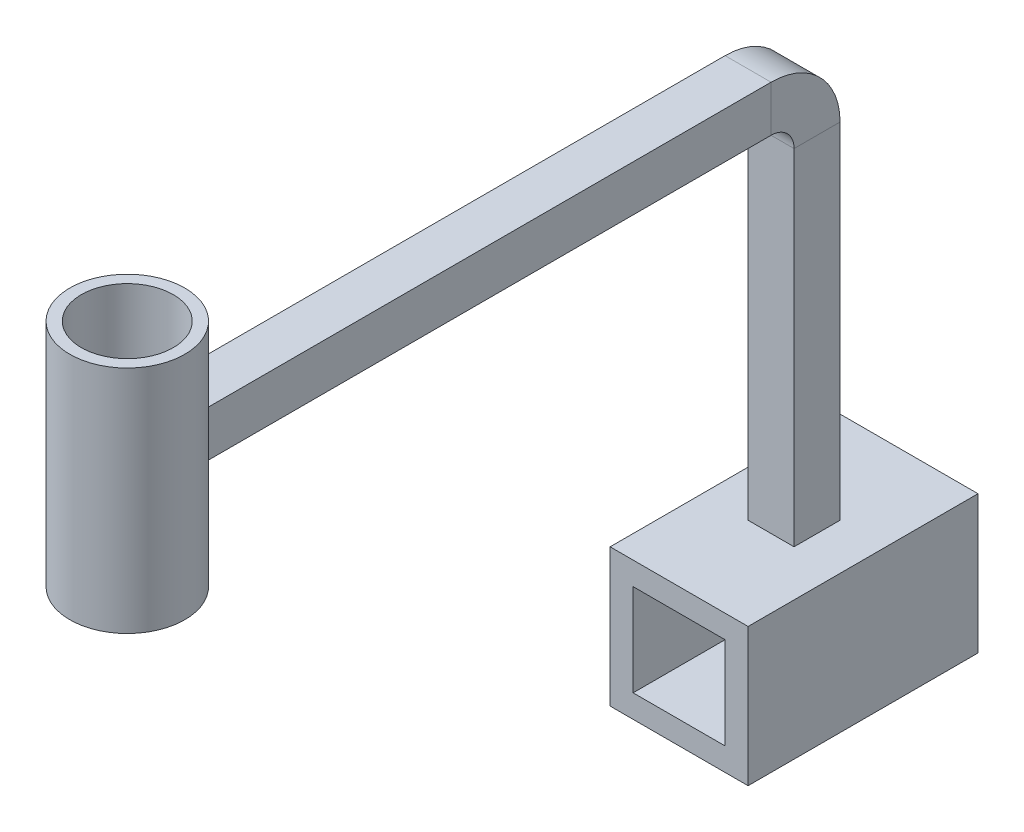
SolidWorks part; units mm, degrees
ref_plane "Plan de face" through (0, 0, 0) normal (0, 0, 1) x (1, 0, 0)
ref_plane "Plan de dessus" through (0, 0, 0) normal (0, 1, 0) x (1, 0, 0)
ref_plane "Plan de droite" through (0, 0, 0) normal (1, 0, 0) x (0, 0, -1)
sketch "Esquisse1" plane through (0, 0, 0) normal (0, 0, 1) x (1, 0, 0)
  line L1 (-2, 2) -> (2, 2)
  line L2 (-2, 2) -> (-2, -2)
  line L3 (-2, -2) -> (2, -2)
  line L4 (2, 2) -> (2, -2)
  line L5 (-2, 2) -> (2, -2) construction
  line L6 (-2, -2) -> (2, 2) construction
  line L7 (-3, 3) -> (3, 3)
  line L8 (-3, 3) -> (-3, -3)
  line L9 (-3, -3) -> (3, -3)
  line L10 (3, 3) -> (3, -3)
  line L11 (-3, 3) -> (3, -3) construction
  line L12 (-3, -3) -> (3, 3) construction
  point P0 (0, 0)
  point P6 (0, 0)
  dimension "D1" = 4
  dimension "D2" = 4
  dimension "D3" = 6
  dimension "D4" = 6
extrude "Boss.-Extru.1" add sketch "Esquisse1" along normal blind 10
sketch "Esquisse2" plane through (0, 3, 0) normal (0, 1, 0) x (1, 0, 0)
  line L0 (0, 0) -> (0, -11.0721) construction
  line L1 (1, -6) -> (-1, -6)
  line L2 (1, -6) -> (1, -4)
  line L3 (1, -4) -> (-1, -4)
  line L4 (-1, -6) -> (-1, -4)
  line L5 (1, -6) -> (-1, -4) construction
  line L6 (1, -4) -> (-1, -6) construction
  line L7 (3, 0) -> (-3, 0) construction
  line L10 (-7.7593, -5) -> (11.5662, -5) construction
  line L11 (3, -10) -> (-3, -10) construction
  point P0 (0, -5)
  point P13 (0, 0)
  dimension "D3" = 2
  dimension "D4" = 2
sketch "Esquisse3" plane through (0, 0, 0) normal (1, 0, 0) x (0, 0, -1)
  line L0 (-5, 3) -> (-5, 18)
  line L1 (-4, 3) -> (-6, 3) construction
  line L2 (-7, 20) -> (-32, 20)
  arc A0 (-5, 18) -> (-7, 20) centre (-7, 18) ccw
  dimension "D1" = 2
  dimension "D2" = 15
  dimension "D3" = 25
sweep "Balayage1" add profiles "Esquisse2" path "Esquisse3"
sketch "Esquisse4" plane through (0, 19, 0) normal (0, -1, 0) x (1, 0, 0)
  line L0 (0, 0) -> (0, 26.1552) construction
  line L1 (-1, 32) -> (1, 32) construction
  circle A0 centre (0, 34) radius 2.5
  circle A1 centre (0, 34) radius 2
  dimension "D1" = 5
  dimension "D2" = 4
  dimension "D3" = 2
extrude "Boss.-Extru.2" add sketch "Esquisse4" along normal blind 4 and the other way blind 6 contours A1 | A0
